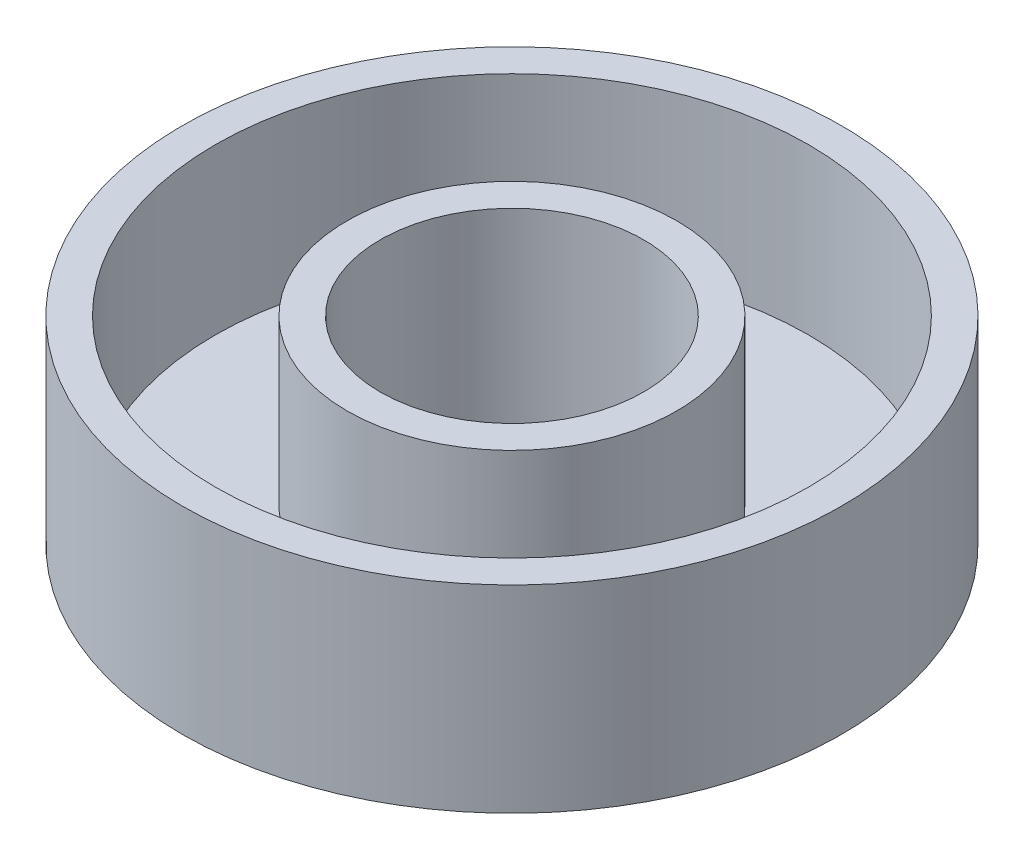
SolidWorks part; units mm, degrees
material "VITON"
ref_plane "Front Plane" through (0, 0, 0) normal (0, 0, 1) x (1, 0, 0)
ref_plane "Top Plane" through (0, 0, 0) normal (0, 1, 0) x (1, 0, 0)
ref_plane "Right Plane" through (0, 0, 0) normal (1, 0, 0) x (0, 0, -1)
sketch "Sketch1" plane through (0, 0, 0) normal (0, 1, 0) x (1, 0, 0)
  circle A0 centre (0, 0) radius 10
  dimension "D1" = 20
extrude "main extrusion" add sketch "Sketch1" along normal blind 6 contours A0
sketch "Sketch2" plane through (0, 6, 0) normal (0, 1, 0) x (1, 0, 0)
  circle A0 centre (0, 0) radius 4
  dimension "D1" = 8
extrude "ID bore" cut sketch "Sketch2" against normal blind 20
sketch "Sketch3" plane through (0, 6, 0) normal (0, 1, 0) x (1, 0, 0)
  circle A0 centre (0, 0) radius 9
  circle A1 centre (0, 0) radius 5
  dimension "D1" = 10
  dimension "D2" = 18
extrude "seal recess" cut sketch "Sketch3" against normal blind 5
equation "\"D1@Sketch1\"=\"seal OD\""
equation "\"D1@main extrusion\" = \"bearing depth\""
equation "\"D1@Sketch2\"=\"seal ID\""
equation "\"bearing OD\" = 20mm"
equation "\"bearing outer race thickness\"= 1mm"
equation "\"bearing ID\"= 10mm"
equation "\"bearing depth\"= 6mm"
equation "\"bearing inner race thickness\"= 1mm"
equation "\"seal OD\" = 20mm"
equation "\"seal ID\"= 8mm"
equation "\"seal depth\"= 6mm"
equation "\"motor to housing distance\"= 60mm"
equation "\"motor mount pattern diameter\"= 30mm"
equation "\"motor mount coupler shaft hole diameter\"= \"coupler shaft base diameter\"+ 4mm"
equation "\"motor mount to housing m8 screw hole diameter\"= 8.5mm"
equation "\"motor mount to housing m8 screw post radius\"= ( 3 * \"motor mount to housing m8 screw hole diameter\" ) / 2"
equation "\"motor mount to housing m8 pattern diameter\"= 100mm"
equation "\"motor mount to housing m4 screw hole diamater\"= 4mm"
equation "\"motor mount to housing m4 head diameter\"= 7.25mm"
equation "\"motor mount to housing m4 head depth\"= 4mm"
equation "\"motor mount plate thickness\"= 6mm + \"motor mount to housing m4 head depth\""
equation "\"motor mount m6 screw hole diameter\"= 6.5mm"
equation "\"motor mount m6 screw socket head diameter\"= 10.5mm"
equation "\"motor mount m6 screw socket head depth\"= 6mm"
equation "\"motor shaft pride\"= 32mm"
equation "\"motor shaft flat section length from tip\"= 25.7mm"
equation "\"motor shaft bore end clearance\"= 2mm"
equation "\"motor mount shaft hole depth\"= \"motor shaft pride\""
equation "\"coupler shaft set screw drill hole diameter\"= 6mm"
equation "\"coupler shaft motor shaft hole diameter\"= 8mm"
equation "\"coupler shaft base diameter\"= 18mm"
equation "\"coupler shaft base length\"= \"motor mount shaft hole depth\" + 10mm"
equation "\"coupler shaft second section diameter\"= \"bearing ID\" + \"bearing inner race thickness\" * 2"
equation "\"coupler shaft third section diamater\"= \"bearing ID\""
equation "\"coupler shaft second section length\"= \"motor to housing distance\" -  \"coupler shaft base length\" - 2mm"
equation "\"coupler shaft set screw 1 distance\"= \"motor mount shaft hole depth\" / 3"
equation "\"coupler shaft set screw 2 distance\"= \"motor mount shaft hole depth\" * 4 / 5"
equation "\"housing bearing seat lip thickness\" = 2mm"
equation "\"housing base thickness\"= \"housing bearing seat lip thickness\" + \"seal depth\" + \"bearing depth\""
equation "\"impeller base outer diameter\"= 1.75in"
equation "\"impeller base outer thickness\"= 1mm"
equation "\"impeller base center thickness\"= 5mm"
equation "\"impeller number of vanes\"= 8"
equation "\"impeller vane outer height`\"= 4mm"
equation "\"impeller vane inner height\"= 8mm"
equation "\"impeller primary vane opening diamater\"= 10mm"
equation "\"impeller shaft bore size\"=4mm "
equation "\"impeller vane inner thickness\"= .75mm"
equation "\"impeller vane outer thickness\"= 1.5mm"
equation "\"impeller primary vane entrance angle\"= 20deg"
equation "\"impeller secondary vane entrance angle\"= 20deg"
equation "\"impeller secondary vane opening diameter\"= 10mm"
equation "\"housing top impeller vertical clearance\"= .5mm"
equation "\"housing top impeller horizontal clearance\"= .5mm"
equation "\"housing top impeller bottom clearance\"= 1mm"
equation "\"housing top impeller cavity height\"= \"housing top impeller bottom clearance\" + \"impeller base center thickness\" + \"impeller vane inner height\" + \"housing top impeller vertical clearance\""
equation "\"housing top impeller cavity diameter\"= 2 * \"housing top impeller horizontal clearance\" + \"impeller base outer diameter\""
equation "\"housing top impeller cavity tip height\"= \"housing top impeller bottom clearance\" + \"housing top impeller vertical clearance\" + \"impeller base outer thickness\" + \"impeller vane outer height\""
equation "\"housing top entrance OD\"= 20mm"
equation "\"housing top exit OD\"= 5mm"
equation "\"housing top o-ring channel height\"= 1.5mm"
equation "\"housing top o ring channel width\"= 1.5mm"
equation "\"housing top threaded inlet depth\"= 8mm"
equation "\"housing top total thickness\"= \"housing top threaded inlet depth\" + \"housing top impeller cavity height\""
equation "\"housing top total width\"= 10mm"
equation "\"housing top exit threaded diameter\"= 8mm"
equation "\"housing top exit threaded depth\"= 8mm"
equation "\"D2@Sketch3\"=\"seal OD\"-2mm"
equation "\"D1@Sketch3\"=\"seal ID\"+2mm"
equation "\"D1@seal recess\"=\"seal depth\"-1mm"
